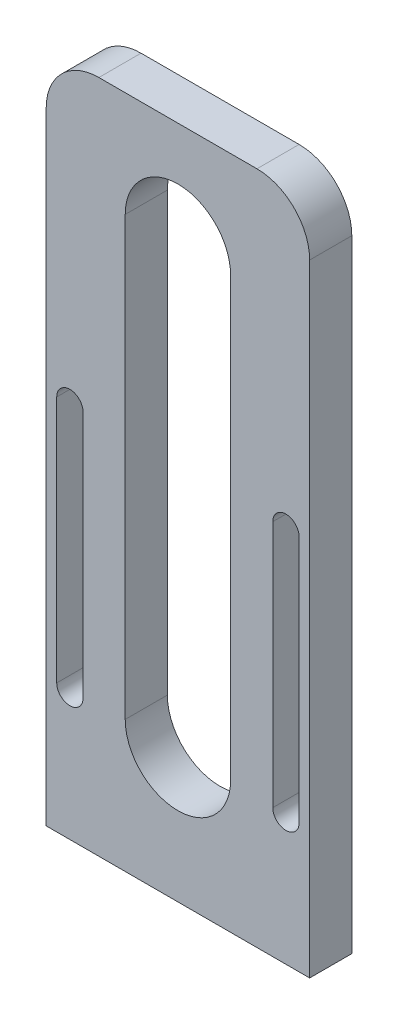
SolidWorks part; units mm, degrees
ref_plane "Płaszczyzna przednia" through (0, 0, 0) normal (0, 0, 1) x (1, 0, 0)
ref_plane "Płaszczyzna górna" through (0, 0, 0) normal (0, 1, 0) x (1, 0, 0)
ref_plane "Płaszczyzna prawa" through (0, 0, 0) normal (1, 0, 0) x (0, 0, -1)
sketch "Szkic1" plane through (0, 0, 0) normal (0, 0, 1) x (1, 0, 0)
  line L0 (0, 0) -> (0, 64) construction
  line L1 (-12.5, 0) -> (12.5, 0)
  line L2 (-12.5, 0) -> (-12.5, 59)
  line L3 (-7.5, 64) -> (7.5, 64)
  line L4 (12.5, 0) -> (12.5, 59)
  line L5 (0, 54) -> (0, 12.5) construction
  line L6 (5, 54) -> (5, 12.5)
  line L7 (-5, 54) -> (-5, 12.5)
  line L8 (-10.25, 35.75) -> (-10.25, 12.25) construction
  line L9 (-9, 35.75) -> (-9, 12.25)
  line L10 (-11.5, 35.75) -> (-11.5, 12.25)
  line L11 (10.25, 35.75) -> (10.25, 12.25) construction
  line L12 (9, 35.75) -> (9, 12.25)
  line L13 (11.5, 35.75) -> (11.5, 12.25)
  arc A0 (7.5, 64) -> (12.5, 59) centre (7.5, 59) cw
  arc A1 (-12.5, 59) -> (-7.5, 64) centre (-7.5, 59) cw
  arc A2 (5, 54) -> (-5, 54) centre (0, 54) ccw
  arc A3 (-5, 12.5) -> (5, 12.5) centre (0, 12.5) ccw
  arc A4 (-9, 35.75) -> (-11.5, 35.75) centre (-10.25, 35.75) ccw
  arc A5 (-11.5, 12.25) -> (-9, 12.25) centre (-10.25, 12.25) ccw
  arc A6 (9, 35.75) -> (11.5, 35.75) centre (10.25, 35.75) cw
  arc A7 (11.5, 12.25) -> (9, 12.25) centre (10.25, 12.25) cw
  point P11 (-12.5, 64)
  point P14 (0, 33.25)
  point P21 (-10.25, 24)
  point P26 (0, 59)
  point P27 (-5, 33.25)
  point P28 (0, 7.5)
  point P29 (-10.25, 11)
  point P30 (-10.25, 37)
  point P33 (10.25, 24)
  dimension "D4" = 5
  dimension "D5" = 5
  dimension "D1" = 64
  dimension "D2" = 64
  dimension "D3" = 25
  dimension "D6" = 10
  dimension "D7" = 51.5
  dimension "D8" = 1
  dimension "D9" = 2.5
  dimension "D10" = 11
  dimension "D11" = 26
extrude "Dodanie-wyciągnięcie1" add sketch "Szkic1" along normal blind 4
